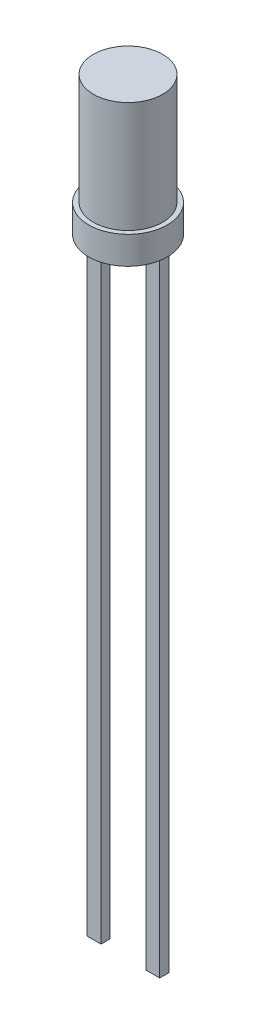
SolidWorks part; units mm, degrees
ref_plane "Front Plane" through (0, 0, 0) normal (0, 0, 1) x (1, 0, 0)
ref_plane "Top Plane" through (0, 0, 0) normal (0, 1, 0) x (1, 0, 0)
ref_plane "Right Plane" through (0, 0, 0) normal (1, 0, 0) x (0, 0, -1)
sketch "Sketch1" plane through (0, 0, 0) normal (0, 1, 0) x (1, 0, 0)
  circle A0 centre (0, 0) radius 1.5
  dimension "D1" = 3
extrude "Boss-Extrude1" add sketch "Sketch1" against normal blind 4.8
sketch "Sketch2" plane through (0, -4.8, 0) normal (0, -1, 0) x (1, 0, 0)
  circle A0 centre (0, 0) radius 1.7
  dimension "D1" = 3.4
extrude "Boss-Extrude2" add sketch "Sketch2" along normal blind 1.2
sketch "Sketch3" plane through (0, -6, 0) normal (0, -1, 0) x (1, 0, 0)
  line L0 (-2.4371, 0) -> (2.8599, 0) construction
  line L2 (-1.57, 0.2) -> (-0.97, 0.2)
  line L3 (-1.57, 0.2) -> (-1.57, -0.2)
  line L4 (-1.57, -0.2) -> (-0.97, -0.2)
  line L5 (-0.97, 0.2) -> (-0.97, -0.2)
  line L6 (-1.57, 0.2) -> (-0.97, -0.2) construction
  line L7 (-1.57, -0.2) -> (-0.97, 0.2) construction
  line L8 (0.97, 0.2) -> (1.57, 0.2)
  line L9 (0.97, 0.2) -> (0.97, -0.2)
  line L10 (0.97, -0.2) -> (1.57, -0.2)
  line L11 (1.57, 0.2) -> (1.57, -0.2)
  line L12 (0.97, 0.2) -> (1.57, -0.2) construction
  line L13 (0.97, -0.2) -> (1.57, 0.2) construction
  point P3 (-1.27, 0)
  point P8 (1.27, 0)
  dimension "D1" = 1.27
  dimension "D2" = 1.27
  dimension "D3" = 0.6
  dimension "D4" = 0.6
  dimension "D5" = 0.4
  dimension "D6" = 0.4
extrude "Boss-Extrude3" add sketch "Sketch3" along normal blind 27
